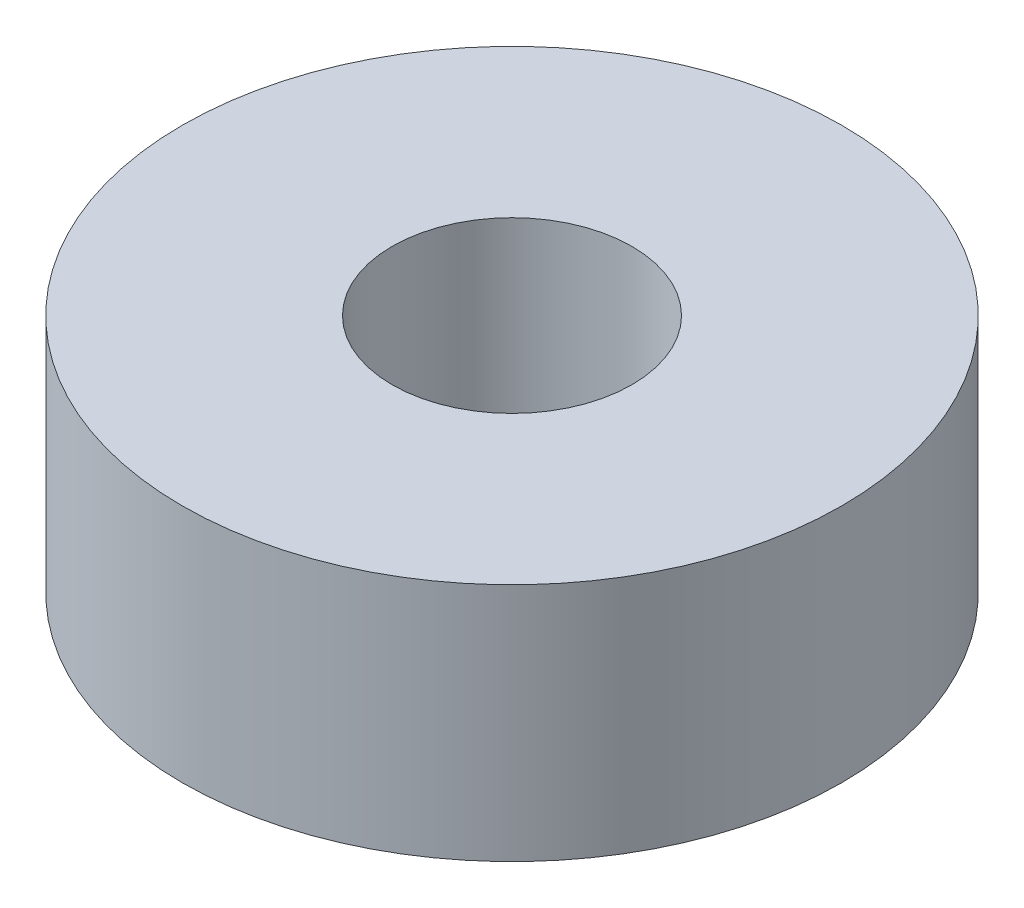
SolidWorks part; units mm, degrees
ref_plane "前基準面" through (0, 0, 0) normal (0, 0, 1) x (1, 0, 0)
ref_plane "上基準面" through (0, 0, 0) normal (0, 1, 0) x (1, 0, 0)
ref_plane "右基準面" through (0, 0, 0) normal (1, 0, 0) x (0, 0, -1)
sketch "草圖1" plane through (0, 0, 0) normal (0, 1, 0) x (1, 0, 0)
  circle A0 centre (0, 0) radius 4
  circle A1 centre (0, 0) radius 11
  dimension "D1" = 22
  dimension "D2" = 8
extrude "填料-伸長1" add sketch "草圖1" along normal blind 8
